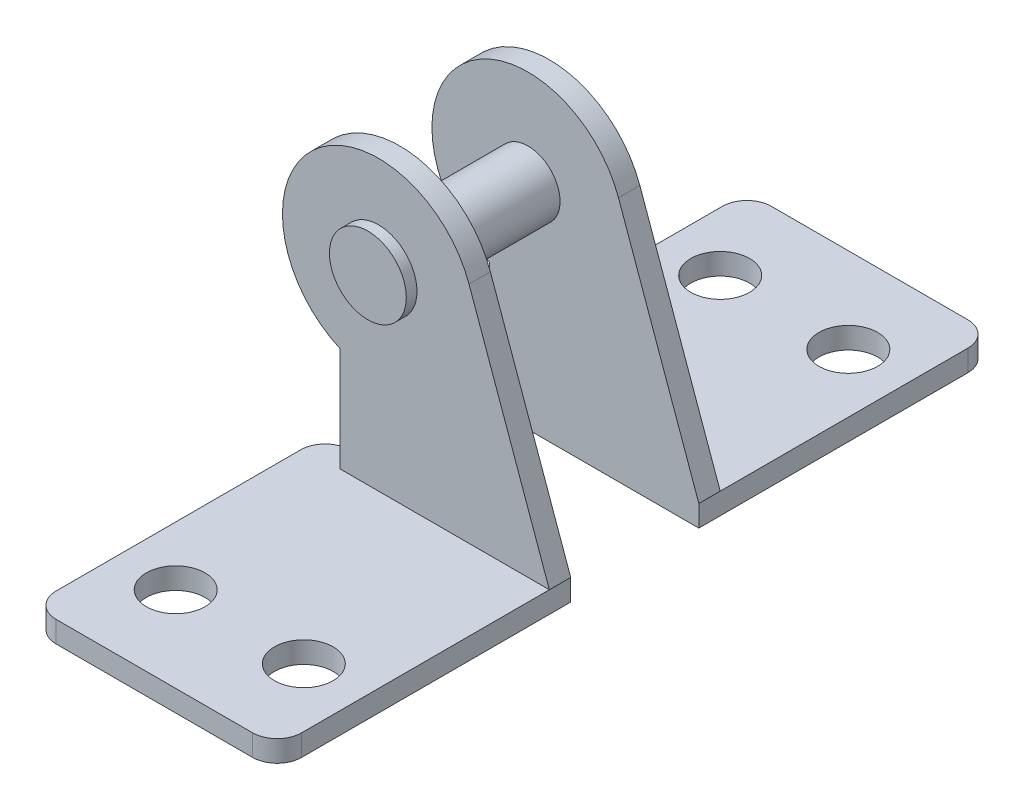
SolidWorks part; units mm, degrees
ref_plane "前视基准面" through (0, 0, 0) normal (0, 0, 1) x (1, 0, 0)
ref_plane "上视基准面" through (0, 0, 0) normal (0, 1, 0) x (1, 0, 0)
ref_plane "右视基准面" through (0, 0, 0) normal (1, 0, 0) x (0, 0, -1)
sketch "草图1" plane through (0, 0, 0) normal (0, 0, 1) x (1, 0, 0)
  line L0 (0, 0) -> (0, 20) construction
  line L1 (-11.5, 0) -> (11.5, 0) construction
  line L2 (3.9738, 23.0323) -> (11.5, 2)
  line L3 (-8.1, 11.7514) -> (-8.1, 0)
  circle A0 centre (-4.5, 20) radius 3
  circle A1 centre (-4.5, 20) radius 9
  point P5 (-6, 0)
  point P6 (-4.5, 20)
  point P7 (-13.5, 20)
  point P12 (0, 2)
  dimension "D1" = 3.6
  dimension "P" = 6
  dimension "CD" = 23
  dimension "CF" = 12
  dimension "CH" = 20
  dimension "D" = 16
  dimension "S" = 9
  dimension "CT" = 2
sketch "草图2" plane through (0, 0, 0) normal (1, 0, 0) x (0, 0, -1)
  line L0 (-33.5, 0) -> (33.5, 0) construction
  line L1 (0, 0) -> (0, 2) construction
  line L2 (0, 0) -> (0, 20) construction
  line L3 (25.5, 0) -> (25.5, 2) construction
  line L4 (0, 11.7514) -> (0, 0) construction
  point P7 (25.5, 0)
  point P8 (-25.5, 0)
  point P11 (22.75, 0)
  point P13 (-8, 0)
  point P14 (-6, 0)
  point P15 (8, 0)
  point P16 (6, 0)
  dimension "CE" = 67
  dimension "CA" = 51
  dimension "CP" = 5.5
  dimension "CQ" = 16
  dimension "Q" = 12
sketch "草图3" plane through (0, 0, 0) normal (0, 0, 1) x (1, 0, 0)
  line L0 (-11.5, 0) -> (-11.5, 2)
  line L1 (-11.5, 2) -> (11.5, 2)
  line L2 (11.5, 2) -> (11.5, 0)
  line L3 (11.5, 0) -> (-11.5, 0)
extrude "凸台-拉伸1" add sketch "草图3" against normal up to vertex (33.5 mm away) from vertex at 33.5 starting at point (0, 0, 33.5)
sketch "草图4" plane through (0, 0, 0) normal (0, 0, 1) x (1, 0, 0)
  line L0 (-8.1, 11.7514) -> (-8.1, 0) construction
  line L1 (3.9738, 23.0323) -> (11.5, 2) construction
  line L2 (-8.1, 11.7514) -> (-8.1, 0)
  line L3 (3.9738, 23.0323) -> (11.5, 2)
  line L4 (-8.1, 0) -> (11.5, 0)
  line L5 (11.5, 0) -> (11.5, 2)
  circle A0 centre (-4.5, 20) radius 9 construction
  circle A1 centre (-4.5, 20) radius 3 construction
  arc A2 (3.9738, 23.0323) -> (-8.1, 11.7514) centre (-4.5, 20) ccw
  circle A3 centre (-4.5, 20) radius 3
extrude "凸台-拉伸2" add sketch "草图4" against normal up to vertex (-6 mm away) from vertex at 8 starting at point (0, 0, 8)
sketch "草图5" plane through (0, 0, 0) normal (0, 0, 1) x (1, 0, 0)
  line L0 (-8.1, 11.7514) -> (-8.1, 0) construction
  line L1 (-8.1, 0) -> (11.5, 0) construction
  line L2 (11.5, 0) -> (11.5, 2) construction
  line L3 (3.9738, 23.0323) -> (11.5, 2) construction
  line L4 (-8.1, 11.7514) -> (-8.1, 0)
  line L5 (-8.1, 0) -> (11.5, 0)
  line L6 (11.5, 0) -> (11.5, 2)
  line L7 (3.9738, 23.0323) -> (11.5, 2)
  circle A0 centre (-4.5, 20) radius 3 construction
  arc A1 (3.9738, 23.0323) -> (-8.1, 11.7514) centre (-4.5, 20) ccw construction
  circle A2 centre (-4.5, 20) radius 3
  arc A3 (3.9738, 23.0323) -> (-8.1, 11.7514) centre (-4.5, 20) ccw
extrude "凸台-拉伸3" add sketch "草图5" along normal up to vertex (-6 mm away) from vertex at -8 starting at point (0, 0, -8)
sketch "草图6" plane through (0, 0, 8) normal (0, 0, 1) x (1, 0, 0)
  circle A0 centre (-4.5, 20) radius 3.6
  dimension "D1" = 7.2
extrude "凸台-拉伸4" add sketch "草图6" along normal blind 1
mirror "镜向2" about plane through (0, 0, 0) normal (0, 0, 1) of "凸台-拉伸4"
sketch "草图7" plane through (0, 0, -8) normal (0, 0, 1) x (1, 0, 0)
  circle A0 centre (-4.5, 20) radius 3 construction
  circle A1 centre (-4.5, 20) radius 3
extrude "凸台-拉伸5" add sketch "草图7" along normal up to surface (16 mm away) up to face at (-1.5, 20, 8)
sketch "草图8" plane through (11.5, 0, 0) normal (1, 0, 0) x (0, 0, -1)
  line L0 (-6, 12.5161) -> (-6, 0)
  line L1 (-6, 2) -> (-6, 23.0323) construction
  line L2 (-6, 0) -> (6, 0)
  line L3 (6, 0) -> (6, 12.5161)
  line L4 (6, 2) -> (6, 23.0323) construction
  line L5 (6, 12.5161) -> (-6, 12.5161)
extrude "切除-拉伸1" cut sketch "草图8" against normal up to surface (23 mm away) up to face at (-11.5, 1, 0)
sketch "草图9" plane through (0, 2, 0) normal (0, 1, 0) x (1, 0, 0)
  line L0 (0, 0) -> (-6, 0) construction
  line L1 (0, 0) -> (0, 22.75) construction
  circle A0 centre (-6, 25.5) radius 2.75
  circle A1 centre (6, 25.5) radius 2.75
  circle A2 centre (6, -25.5) radius 2.75
  circle A3 centre (-6, -25.5) radius 2.75
  point P2 (-6, 22.75)
  point P12 (6, 22.75)
extrude "切除-拉伸2" cut sketch "草图9" against normal through all
fillet "圆角3" radius 2.3 6 edges at (11.5, 1, -33.5) (-11.5, 1, -33.5) (-11.5, 1, 33.5) (11.5, 1, 33.5) (-11.5, 1, 6) (-11.5, 1, -6)
